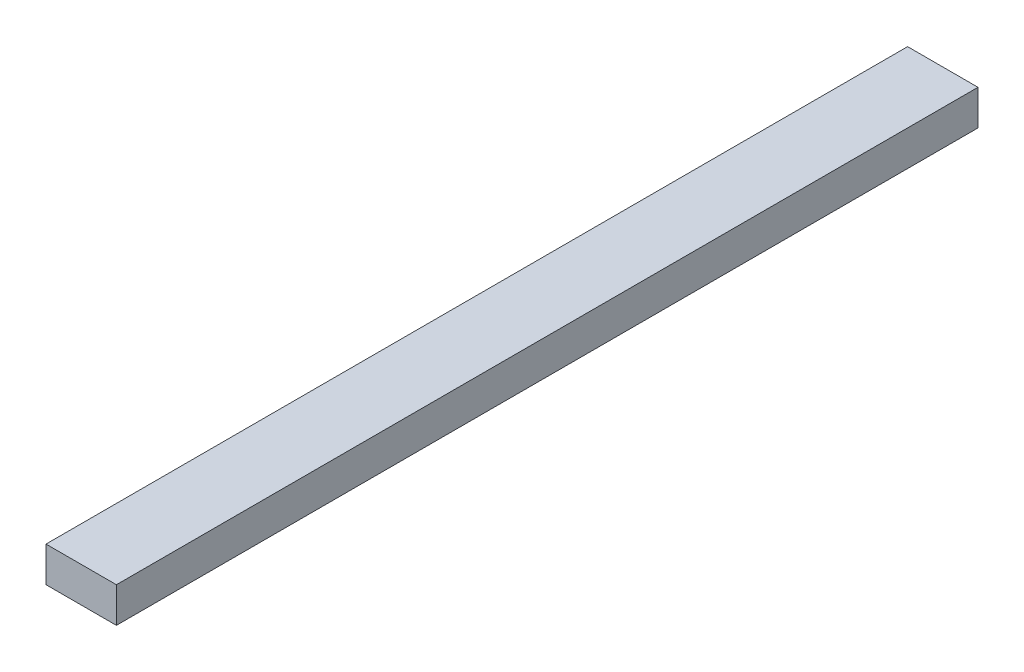
SolidWorks part; units mm, degrees
ref_plane "Front Plane" through (0, 0, 0) normal (0, 0, 1) x (1, 0, 0)
ref_plane "Top Plane" through (0, 0, 0) normal (0, 1, 0) x (1, 0, 0)
ref_plane "Right Plane" through (0, 0, 0) normal (1, 0, 0) x (0, 0, -1)
sketch "Sketch1" plane through (0, 0, 0) normal (0, 0, 1) x (1, 0, 0)
  line L1 (-25.4, -12.7) -> (25.4, -12.7)
  line L2 (-25.4, -12.7) -> (-25.4, 12.7)
  line L3 (-25.4, 12.7) -> (25.4, 12.7)
  line L4 (25.4, -12.7) -> (25.4, 12.7)
  line L5 (-25.4, -12.7) -> (25.4, 12.7) construction
  line L6 (-25.4, 12.7) -> (25.4, -12.7) construction
  point P0 (0, 0)
  dimension "D1" = 25.4
  dimension "D2" = 50.8
extrude "Boss-Extrude1" add sketch "Sketch1" along normal blind 609.6
sketch "Sketch2" plane through (0, 0, 609.6) normal (0, 0, 1) x (1, 0, 0)
  line L4 (25.4, -12.7) -> (25.4, 12.7)
  line L5 (25.4, 12.7) -> (-25.4, 12.7)
  line L6 (-25.4, 12.7) -> (-25.4, -12.7)
  line L7 (-25.4, -12.7) -> (25.4, -12.7)
  line L8 (25.4, -12.7) -> (25.4, 12.7)
  line L9 (25.4, 12.7) -> (-25.4, 12.7)
  line L10 (-25.4, 12.7) -> (-25.4, -12.7)
  line L11 (-25.4, -12.7) -> (25.4, -12.7)
  dimension "D1" = 0
extrude "Boss-Extrude2" add sketch "Sketch2" along normal blind 12
